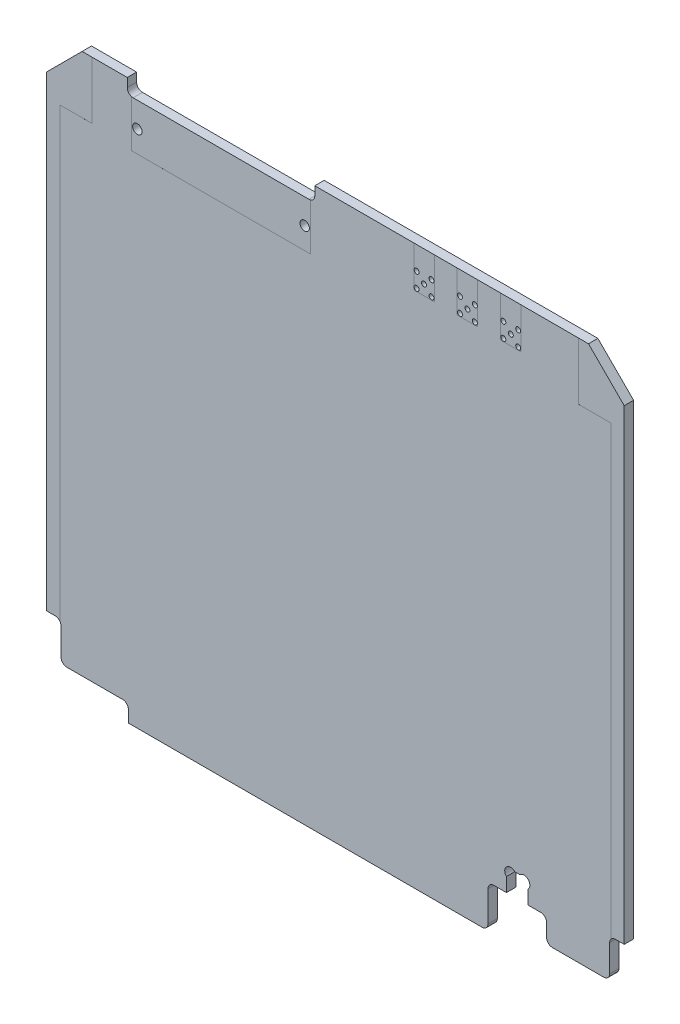
SolidWorks part; units mm, degrees
ref_plane "Front Plane" through (0, 0, 0) normal (0, 0, 1) x (1, 0, 0)
ref_plane "Top Plane" through (0, 0, 0) normal (0, 1, 0) x (1, 0, 0)
ref_plane "Right Plane" through (0, 0, 0) normal (1, 0, 0) x (0, 0, -1)
ref_plane "Plane4" through (0, 0, -0.0125) normal (0, 0, -1) x (-1, 0, 0)
sketch "Sketch1" plane through (0, 0, -0.0125) normal (0, 0, -1) x (-1, 0, 0)
  line L0 (35.3, -50) -> (35.3, -48)
  line L1 (36.3, -47) -> (45.8, -47)
  line L2 (46.8, -46) -> (46.8, -41.4)
  line L3 (47.8, -40.4) -> (49.3, -40.4)
  line L4 (49.3, -40.4) -> (49.3, 39.2)
  line L5 (49.3, 39.2) -> (43.2, 45.3)
  line L6 (43.2, 45.3) -> (35.5, 45.3)
  line L7 (35.5, 45.3) -> (35.5, 43.8)
  line L8 (34.5, 42.8) -> (4.5, 42.8)
  line L9 (3.5, 43.8) -> (3.5, 45.3)
  line L10 (3.5, 45.3) -> (-43.2, 45.3)
  line L11 (-43.2, 45.3) -> (-49.3, 39.2)
  line L12 (-49.3, 39.2) -> (-49.3, -40.4)
  line L13 (-49.3, -40.4) -> (-47.8, -40.4)
  line L14 (-46.8, -41.4) -> (-46.8, -46)
  line L15 (-45.8, -47) -> (-36.3, -47)
  line L16 (-35.3, -48) -> (-35.3, -50)
  line L17 (-35.3, -50) -> (35.3, -50)
  line L18 (0, -50) -> (0, 45.3) construction
  line L19 (19.5, 42.8) -> (19.5, 25.5258) construction
  line L20 (-13.87, 41.37) -> (-16.41, 38.83) construction
  line L21 (-21.27, 41.37) -> (-23.81, 38.83) construction
  line L22 (-28.67, 41.37) -> (-31.21, 38.83) construction
  arc A0 (35.3, -48) -> (36.3, -47) centre (36.3, -48) cw
  arc A1 (45.8, -47) -> (46.8, -46) centre (45.8, -46) ccw
  arc A2 (46.8, -41.4) -> (47.8, -40.4) centre (47.8, -41.4) cw
  arc A3 (35.5, 43.8) -> (34.5, 42.8) centre (34.5, 43.8) cw
  arc A4 (4.5, 42.8) -> (3.5, 43.8) centre (4.5, 43.8) cw
  arc A5 (-47.8, -40.4) -> (-46.8, -41.4) centre (-47.8, -41.4) cw
  arc A6 (-46.8, -46) -> (-45.8, -47) centre (-45.8, -46) ccw
  arc A7 (-36.3, -47) -> (-35.3, -48) centre (-36.3, -48) cw
  circle A8 centre (-21.27, 41.37) radius 0.425
  circle A9 centre (-23.81, 41.37) radius 0.425
  circle A10 centre (-22.54, 40.1) radius 0.425
  circle A11 centre (-13.87, 41.37) radius 0.425
  circle A12 centre (-23.81, 38.83) radius 0.425
  circle A13 centre (-16.41, 41.37) radius 0.425
  circle A14 centre (-15.14, 40.1) radius 0.425
  circle A15 centre (-21.27, 38.83) radius 0.425
  circle A16 centre (-28.67, 41.37) radius 0.425
  circle A17 centre (-31.21, 41.37) radius 0.425
  circle A18 centre (-16.41, 38.83) radius 0.425
  circle A19 centre (-29.94, 40.1) radius 0.425
  circle A20 centre (-31.21, 38.83) radius 0.425
  circle A21 centre (-28.67, 38.83) radius 0.425
  circle A22 centre (33.775, 38.54) radius 0.8
  circle A23 centre (5.225, 38.54) radius 0.8
  circle A24 centre (-13.87, 38.83) radius 0.425
  point P35 (-15.14, 40.1)
  dimension "D7" = 2.5
  dimension "D8" = 1.6
  dimension "D9" = 14.275
  dimension "D10" = 4.26
  dimension "D11" = 1
  dimension "D12" = 1
  dimension "D13" = 1
  dimension "D14" = 1
  dimension "D15" = 1
  dimension "D16" = 1
  dimension "D17" = 1
  dimension "D18" = 1
  dimension "D26" = 0.85
  dimension "D1" = 98.6
  dimension "D2" = 95.3
  dimension "D3" = 14
  dimension "D4" = 9.6
  dimension "D5" = 2.5
  dimension "D6" = 3
  dimension "D19" = 14
  dimension "D20" = 2.5
  dimension "D21" = 6.1
  dimension "D22" = 6.1
  dimension "D23" = 32
  dimension "D24" = 2.54
  dimension "D25" = 2.54
  dimension "D28" = 7.4
  dimension "D29" = 3.93
  dimension "D30" = 35.43
  dimension "D31" = 45
  dimension "D32" = 45
  dimension "D33" = 29.8
  dimension "D34" = 50
  dimension "D27" = 3
extrude "Boss-Extrude1" add sketch "Sketch1" against normal blind 1.6
sketch "thermalContacts_lower" plane through (0, 0, -0.0125) normal (0, 0, -1) x (-1, 0, 0)
  line L0 (47, 35.5) -> (47, -41.5) construction
  line L1 (41.5, 35.5) -> (41.5, 41.5) construction
  line L2 (41.5, 35.5) -> (47, 35.5) construction
  line L3 (47, 35.5) -> (47, -41.5)
  line L4 (41.5, 35.5) -> (41.5, 41.5)
  line L5 (41.5, 35.5) -> (47, 35.5)
  line L6 (-47, 35.5) -> (-47, -41.5) construction
  line L7 (-41.5, 35.5) -> (-47, 35.5) construction
  line L8 (-41.5, 35.5) -> (-41.5, 41.5) construction
  line L9 (-47, 35.5) -> (-47, -41.5)
  line L10 (-41.5, 35.5) -> (-47, 35.5)
  line L11 (-41.5, 35.5) -> (-41.5, 41.5)
  line L12 (-41.5, 41.5) -> (-41.5, 47) construction
  line L13 (-41.5, 41.5) -> (-49.5, 41.5) construction
  line L14 (-41.5, 41.5) -> (-41.5, 47)
  line L15 (-41.5, 41.5) -> (-49.5, 41.5) construction
  line L16 (41.5, 41.5) -> (41.5, 47) construction
  line L17 (41.5, 41.5) -> (49.5, 41.5) construction
  line L18 (41.5, 41.5) -> (41.5, 47)
  line L19 (41.5, 41.5) -> (49.5, 41.5) construction
  line L20 (47, -41.5) -> (59.8273, -41.5)
  line L21 (59.8273, -41.5) -> (59.8273, 47)
  line L22 (-56.1922, 47) -> (-41.5, 47)
  line L23 (41.5, 47) -> (59.8273, 47)
  line L24 (-56.1922, 47) -> (-56.1922, -41.5)
  line L25 (-47, -41.5) -> (-56.1922, -41.5)
sketch "thermalContacts_upper" plane through (0, 0, 1.5875) normal (0, 0, 1) x (1, 0, 0)
  line L3 (-47, 35.5) -> (-47, -41.5)
  line L4 (-41.5, 35.5) -> (-41.5, 41.5)
  line L5 (-41.5, 35.5) -> (-47, 35.5)
  line L9 (47, 35.5) -> (47, -41.5)
  line L10 (41.5, 35.5) -> (47, 35.5)
  line L11 (41.5, 35.5) -> (41.5, 41.5)
  line L14 (41.5, 41.5) -> (41.5, 47)
  line L15 (41.5, 41.5) -> (49.5, 41.5) construction
  line L18 (-41.5, 41.5) -> (-41.5, 47)
  line L19 (-41.5, 41.5) -> (-49.5, 41.5) construction
  line L20 (47, -41.5) -> (59.8273, -41.5)
  line L21 (59.8273, -41.5) -> (59.8273, 47)
  line L22 (59.8273, 47) -> (41.5, 47)
  line L23 (-41.5, 47) -> (-56.1922, 47)
  line L24 (-56.1922, 47) -> (-56.1922, -41.5)
  line L25 (-56.1922, -41.5) -> (-47, -41.5)
extrude "Cut-Extrude1" cut sketch "thermalContacts_lower" against normal blind 0.0001
extrude "Cut-Extrude2" cut sketch "thermalContacts_upper" against normal blind 0.0001
sketch "partFootprints" plane through (0, 0, 1.5875) normal (0, 0, 1) x (1, 0, 0)
  line L0 (-34.74, 34.84) -> (-34.74, 42.8292)
  line L1 (-4.26, 34.84) -> (-34.74, 34.84)
  line L2 (-41.5, 45.3) -> (-35.5, 45.3) construction
  line L3 (-36.1132, 45.3) -> (-39.5054, 45.3) construction
  line L4 (-4.26, 34.84) -> (-4.26, 42.8292)
  line L5 (-49.3, -40.4) -> (-49.3, 39.2) construction
  line L6 (13.39, 45.3) -> (13.39, 38.35)
  line L7 (13.39, 38.35) -> (16.89, 38.35)
  line L8 (16.89, 38.35) -> (16.89, 45.3)
  line L9 (16.89, 45.3) -> (13.39, 45.3)
  line L10 (20.79, 45.3) -> (20.79, 38.35)
  line L11 (20.79, 38.35) -> (24.29, 38.35)
  line L12 (24.29, 38.35) -> (24.29, 45.3)
  line L13 (24.29, 45.3) -> (20.79, 45.3)
  line L14 (28.19, 45.3) -> (28.19, 38.35)
  line L15 (28.19, 38.35) -> (31.69, 38.35)
  line L16 (31.69, 38.35) -> (31.69, 45.3)
  line L17 (31.69, 45.3) -> (28.19, 45.3)
  line L19 (14.12, 38.35) -> (16.16, 38.35) construction
  line L20 (-34.74, 42.8292) -> (-4.26, 42.8292)
  line L21 (-3.5, 45.3) -> (41.5, 45.3) construction
  line L22 (14.12, 38.35) -> (16.16, 38.35) construction
  line L23 (13.39, 41.85) -> (13.39, 38.35) construction
  line L24 (16.89, 41.85) -> (16.89, 38.35) construction
  line L25 (13.39, 41.85) -> (13.39, 38.35) construction
  line L26 (16.89, 41.85) -> (16.89, 38.35) construction
  arc A0 (-35.5, 43.8) -> (-34.5, 42.8) centre (-34.5, 43.8) ccw construction
  arc A1 (-4.5, 42.8) -> (-3.5, 43.8) centre (-4.5, 43.8) ccw construction
  dimension "D1" = 10.46
  dimension "D2" = 14.56
  dimension "D3" = 30.48
  dimension "D7" = 7.4
  dimension "D6" = 3
extrude "Cut-Extrude3" cut sketch "partFootprints" against normal blind 0.0001
sketch "Sketch2" plane through (0, 0, 1.5875) normal (0, 0, 1) x (1, 0, 0)
  line L0 (35.1, -50) -> (35.1, -37.5518) construction
  line L1 (35.3, -50) -> (-35.3, -50) construction
  line L2 (27, -50) -> (27, -36.9095) construction
  line L3 (35.3, -48) -> (35.3, -50) construction
  line L4 (29.2, -42.8) -> (29.2, -40.4142)
  line L5 (27, -39) -> (35.1, -39) construction
  line L6 (30.6142, -39) -> (31.4858, -39)
  line L7 (32.9, -40.4142) -> (32.9, -42.8)
  line L8 (26.05, -50) -> (36.05, -50)
  line L9 (30.6142, -39) -> (31.4858, -39) construction
  line L10 (26.05, -50) -> (26.05, -42.8)
  line L11 (26.05, -42.8) -> (29.2, -42.8)
  line L12 (31.05, -39) -> (31.05, -50) construction
  line L13 (36.05, -42.8) -> (32.9, -42.8)
  line L14 (36.05, -50) -> (36.05, -42.8)
  line L15 (48.0683, 27.2) -> (36.7758, 27.2) construction
  line L16 (48.0683, 35.5) -> (35.6387, 35.5) construction
  line L17 (42.1, 29.55) -> (39.0071, 29.55) construction
  line L18 (38.3, 35.5) -> (38.3, 27.2) construction
  line L19 (38.3, 30.2571) -> (38.3, 32.4429) construction
  line L20 (39.0071, 33.15) -> (42.1, 33.15) construction
  line L21 (49.3, 29.1) -> (49.3, 33.6) construction
  line L22 (38.3, 30.2571) -> (38.3, 32.4429) construction
  line L23 (49.3, 29.1) -> (42.1, 29.1) construction
  line L24 (42.1, 29.1) -> (42.1, 29.55) construction
  line L25 (38.3, 31.35) -> (49.3, 31.35) construction
  line L26 (42.1, 33.6) -> (42.1, 33.15) construction
  line L27 (49.3, 33.6) -> (42.1, 33.6) construction
  line L28 (49.3, -40.4) -> (49.3, 39.2) construction
  line L30 (31.69, 45.3) -> (41.5, 45.3) construction
  arc A0 (29.2, -40.4142) -> (30.6142, -39) centre (29.9071, -39.7071) cw
  arc A1 (31.4858, -39) -> (32.9, -40.4142) centre (32.1929, -39.7071) cw
  arc A2 (39.0071, 29.55) -> (38.3, 30.2571) centre (38.6536, 29.9036) cw construction
  arc A3 (38.3, 32.4429) -> (39.0071, 33.15) centre (38.6536, 32.7964) cw construction
  point P8 (35.3, -49)
  point P39 (38.3, 31.35)
  point P46 (38.3, 31.35)
  point P47 (38.3, 29.55)
  point P48 (38.3, 33.15)
  point P57 (31.05, -39)
  point P59 (32.9, -39)
  point P60 (29.2, -39)
  dimension "D5" = 1
  dimension "D8" = 0.5
  dimension "D1" = 0.2
  dimension "D2" = 8.3
  dimension "D3" = 3.7
  dimension "D4" = 11
  dimension "D6" = 3.8
  dimension "D7" = 10
  dimension "D9" = 3.6
  dimension "D10" = 11
  dimension "D11" = 3.8
  dimension "D12" = 4.5
  dimension "D13" = 9.8
  dimension "D14" = 8.3
extrude "Cut-Extrude4" cut sketch "Sketch2" against normal through all
sketch "Sketch3" plane through (0, 0, 1.5875) normal (0, 0, 1) x (1, 0, 0)
  line L0 (45.8, -47) -> (36.3, -47) construction
  line L1 (31.741, -47) -> (39.5208, -47)
  line L2 (31.741, -47) -> (31.741, -52.1552)
  line L3 (31.741, -52.1552) -> (39.5208, -52.1552)
  line L4 (39.5208, -47) -> (39.5208, -52.1552)
extrude "Cut-Extrude5" cut sketch "Sketch3" against normal blind 10
fillet "Fillet1" radius 1 4 edges at (36.05, -42.8, 0.7875) (26.05, -42.8, 0.7875) (36.05, -47, 0.7875) (26.05, -50, 0.7875)
